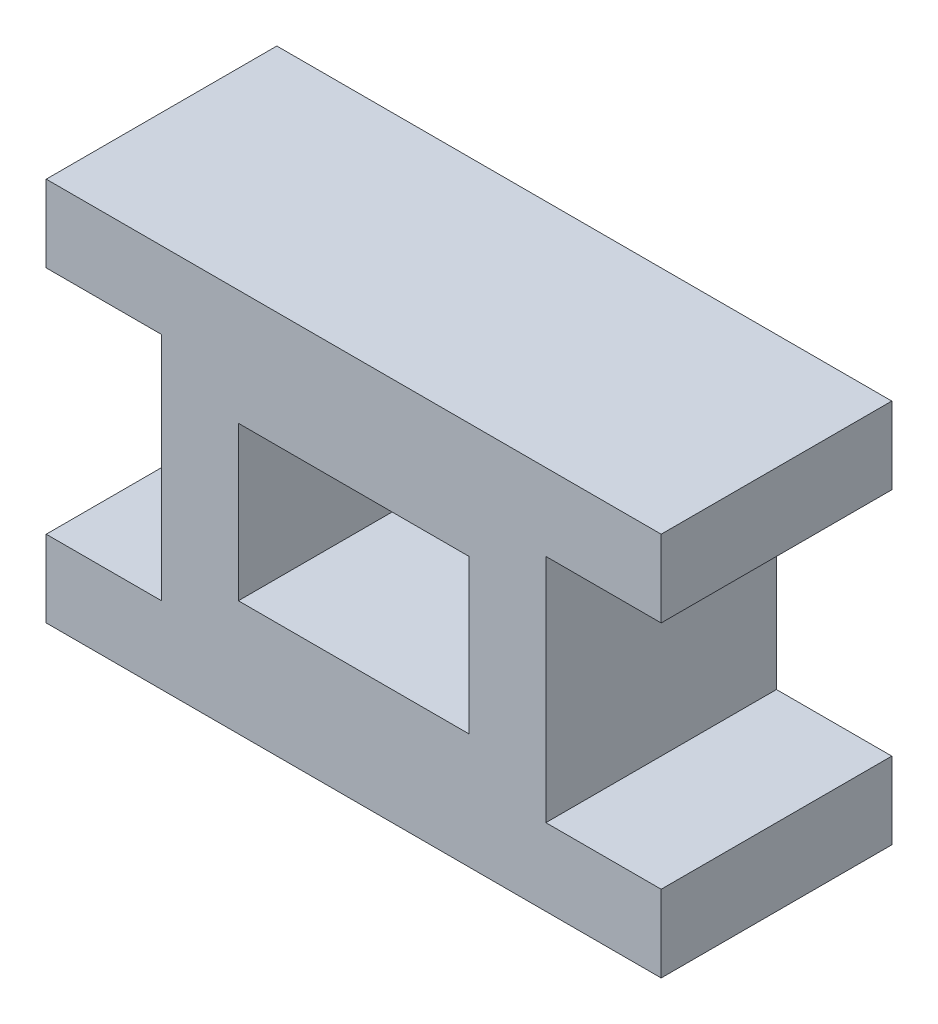
SolidWorks part; units mm, degrees
ref_plane "Front Plane" through (0, 0, 0) normal (0, 0, 1) x (1, 0, 0)
ref_plane "Top Plane" through (0, 0, 0) normal (0, 1, 0) x (1, 0, 0)
ref_plane "Right Plane" through (0, 0, 0) normal (1, 0, 0) x (0, 0, -1)
sketch "Sketch1" plane through (0, 0, 0) normal (0, 0, 1) x (1, 0, 0)
  line L0 (0, 0) -> (20930.7907, 0) construction
  line L1 (0, 0) -> (0, -20930.7907) construction
  line L2 (-40, 15) -> (-25, 15)
  line L3 (-40, -25) -> (40, -25)
  line L4 (-40, -25) -> (-40, -15)
  line L5 (-40, 25) -> (40, 25)
  line L6 (40, -25) -> (40, -15)
  line L7 (-40, -25) -> (40, 25) construction
  line L8 (-40, 25) -> (40, -25) construction
  line L9 (-15, -10) -> (15, -10)
  line L10 (-15, -10) -> (-15, 10)
  line L11 (-15, 10) -> (15, 10)
  line L12 (15, -10) -> (15, 10)
  line L13 (-15, -10) -> (15, 10) construction
  line L14 (-15, 10) -> (15, -10) construction
  line L15 (-25, 15) -> (-25, -15)
  line L16 (-25, -15) -> (-40, -15)
  line L17 (25, -15) -> (40, -15)
  line L18 (25, 15) -> (25, -15)
  line L19 (40, 15) -> (25, 15)
  line L20 (-40, 15) -> (-40, 25)
  line L21 (40, 15) -> (40, 25)
  point P5 (0, 0)
  point P10 (0, 0)
  dimension "D1" = 80
  dimension "D2" = 50
  dimension "D3" = 30
  dimension "D4" = 20
  dimension "D5" = 10
  dimension "D6" = 10
extrude "Boss-Extrude1" add sketch "Sketch1" along normal mid plane 30
